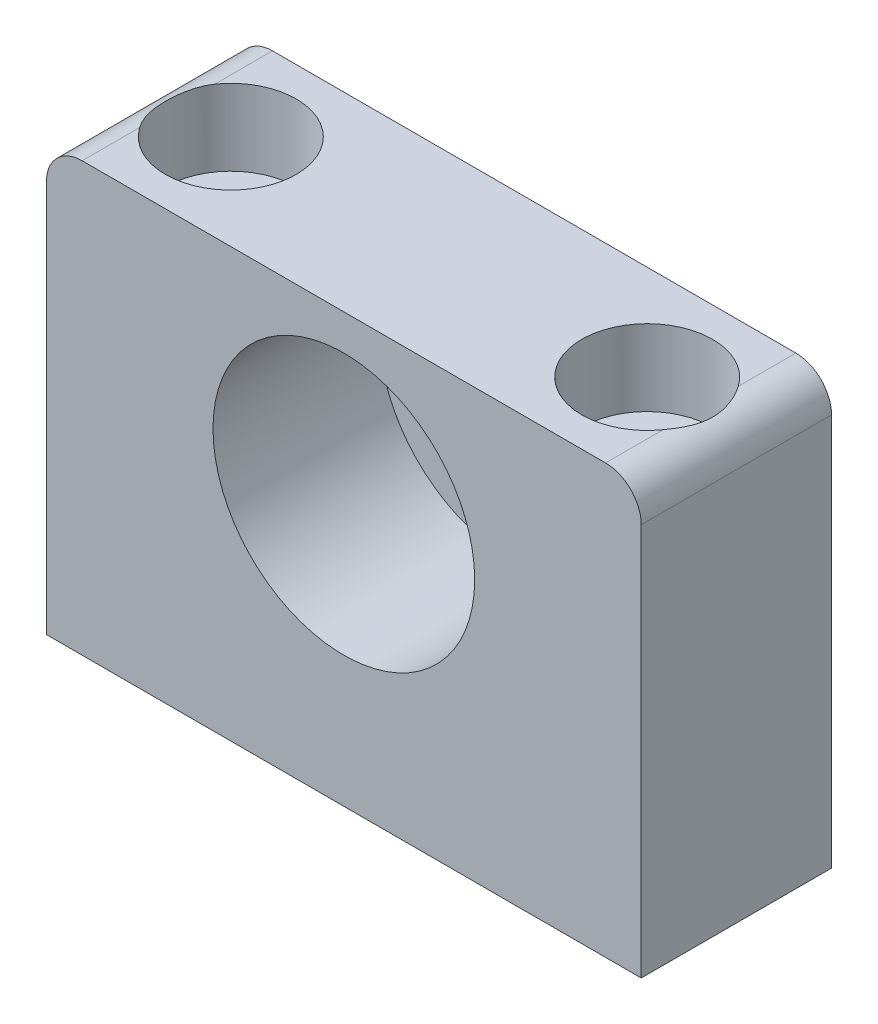
SolidWorks part; units mm, degrees
material "3.3315 (EN-AW 5005)"
ref_plane "Спереди" through (0, 0, 0) normal (0, 0, 1) x (1, 0, 0)
ref_plane "Сверху" through (0, 0, 0) normal (0, 1, 0) x (1, 0, 0)
ref_plane "Справа" through (0, 0, 0) normal (1, 0, 0) x (0, 0, -1)
sketch "Эскиз8" plane through (0, 0, 0) normal (0, 0, 1) x (1, 0, 0)
  line L1 (-22, 18) -> (22, 18)
  line L2 (-25, 15) -> (-25, -18)
  line L3 (-25, -18) -> (25, -18)
  line L4 (25, 15) -> (25, -18)
  line L5 (-25, 18) -> (25, -18) construction
  line L6 (-25, -18) -> (25, 18) construction
  arc A0 (22, 18) -> (25, 15) centre (22, 15) cw
  arc A1 (-22, 18) -> (-25, 15) centre (-22, 15) ccw
  point P0 (0, 0)
  dimension "D2" = 3
  dimension "D1" = 50
  dimension "D3" = 36
extrude "База" add sketch "Эскиз8" against normal blind 16
hole_wizard "Крепление-М6" positions "Эскиз12" profile "Эскиз11" counterbore size "M6" standard "ISO" end condition through all
sketch "Эскиз12" plane through (0, 18, 0) normal (0, 1, 0) x (1, 0, 0)
  line L4 (-25, 8) -> (-17.5, 8) construction
  line L5 (-25, 16) -> (-25, 0) construction
  line L8 (17.5, 8) -> (25, 8) construction
  line L9 (25, 16) -> (25, 0) construction
  point P0 (-17.5, 8)
  point P2 (17.5, 8)
  dimension "D1" = 7.5
sketch "Эскиз11" plane through (-17.5, 18, -8) normal (1, 0, 0) x (0, 0, 1)
  line L0 (0, 0) -> (0, 36)
  line L1 (0, 36) -> (3.3, 36)
  line L2 (3.3, 6.425) -> (3.3, 36)
  line L3 (3.3, 6.425) -> (3.325, 6.4)
  line L4 (3.325, 6.4) -> (5.5, 6.4)
  line L5 (5.5, 6.4) -> (5.5, 0)
  line L7 (0, 0) -> (5.5, 0)
  line L9 (-3.3, 6.425) -> (-3.325, 6.4) construction
  line L11 (0, -6.35) -> (0, 107.95) construction
  dimension "Диаметр сквозного отверстия" = 6.6
  dimension "Thru Hole Depth" = 36
  dimension "Диаметр цековки" = 11
  dimension "Глубина цековки" = 6.4
  dimension "Диаметр средней зенковки" = 6.65
  dimension "Угол средней зенковки" = 90
sketch "Эскиз14" plane through (0, 0, 0) normal (0, 0, 1) x (1, 0, 0)
  line L0 (-25, -18) -> (25, -18) construction
  circle A0 centre (0, 4) radius 11
  dimension "D1" = 22
  dimension "D2" = 22
extrude "Вырез-608" cut sketch "Эскиз14" against normal blind 14
